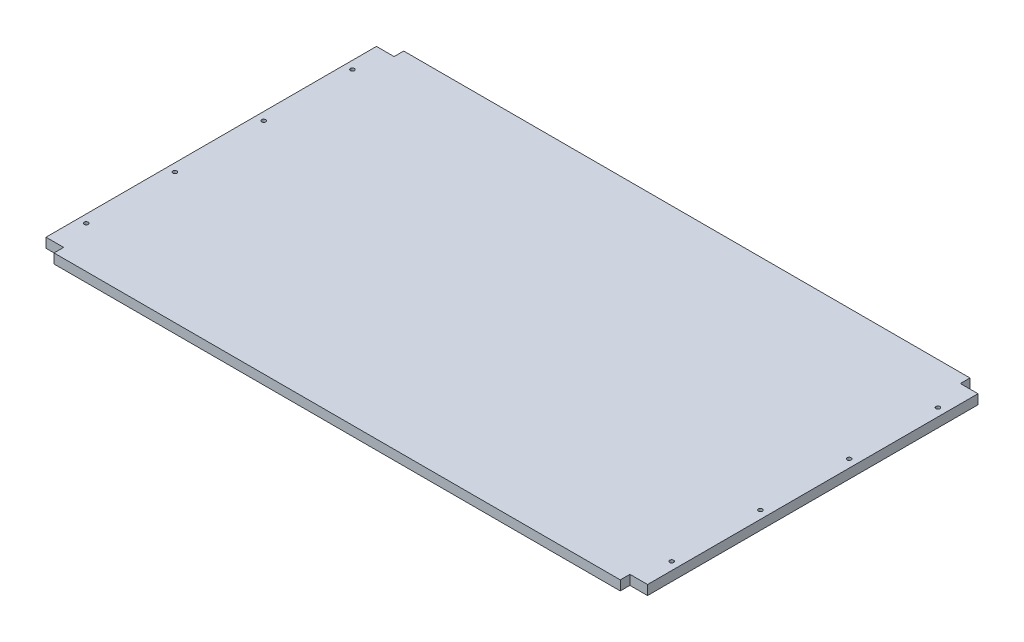
SolidWorks part; units mm, degrees
ref_plane "Front Plane" through (0, 0, 0) normal (0, 0, 1) x (1, 0, 0)
ref_plane "Top Plane" through (0, 0, 0) normal (0, 1, 0) x (1, 0, 0)
ref_plane "Right Plane" through (0, 0, 0) normal (1, 0, 0) x (0, 0, -1)
sketch "Sketch1" plane through (0, 0, 0) normal (0, 1, 0) x (1, 0, 0)
  line L0 (0, 0) -> (0, 12)
  line L1 (0, 12) -> (-22, 12)
  line L2 (-22, 12) -> (-22, 424)
  line L3 (-22, 424) -> (0, 424)
  line L4 (0, 424) -> (0, 436)
  line L5 (0, 436) -> (706, 436)
  line L6 (706, 436) -> (706, 424)
  line L7 (706, 424) -> (728, 424)
  line L8 (728, 424) -> (728, 12)
  line L9 (728, 12) -> (706, 12)
  line L10 (706, 12) -> (706, 0)
  line L11 (0, 0) -> (706, 0)
  line L12 (-12, 52) -> (-12, 384) construction
  line L13 (-22, 218) -> (728, 218) construction
  line L14 (353, 0) -> (353, 669.707) construction
  circle A0 centre (-12, 52) radius 2.5
  circle A1 centre (-12, 162.6667) radius 2.5
  circle A2 centre (-12, 273.3333) radius 2.5
  circle A3 centre (-12, 384) radius 2.5
  circle A4 centre (718, 384) radius 2.5
  circle A5 centre (718, 273.3333) radius 2.5
  circle A6 centre (718, 162.6667) radius 2.5
  circle A7 centre (718, 52) radius 2.5
  point P17 (-12, 218)
  point P28 (-11, 424)
  dimension "D8" = 5
  dimension "D1" = 436
  dimension "D2" = 750
  dimension "D3" = 12
  dimension "D4" = 22
  dimension "D5" = 10
  dimension "D7" = 40
  dimension "D6" = 4
extrude "Boss-Extrude1" add sketch "Sketch1" along normal blind 12
